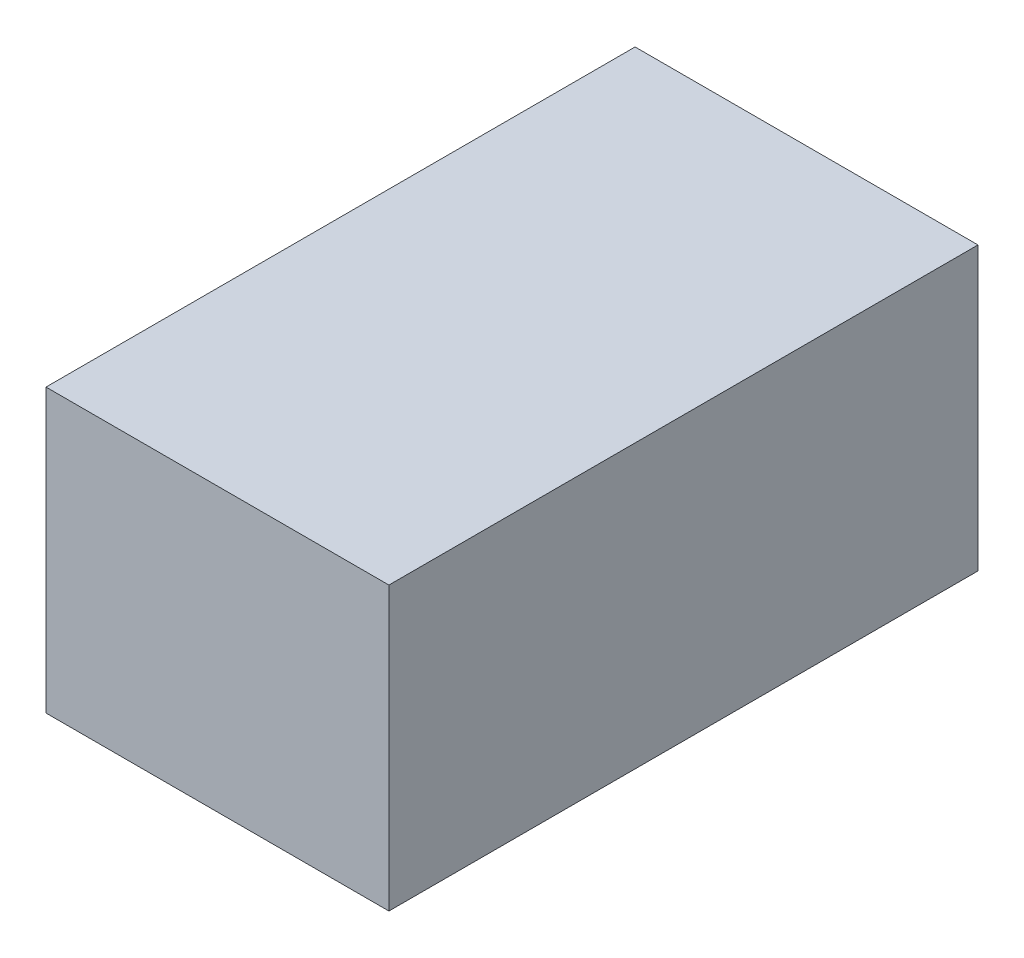
SolidWorks part; units mm, degrees
ref_plane "Front Plane" through (0, 0, 0) normal (0, 0, 1) x (1, 0, 0)
ref_plane "Top Plane" through (0, 0, 0) normal (0, 1, 0) x (1, 0, 0)
ref_plane "Right Plane" through (0, 0, 0) normal (1, 0, 0) x (0, 0, -1)
sketch "Sketch1" plane through (0, 0, 0) normal (0, 1, 0) x (1, 0, 0)
  line L1 (0, 0) -> (140.462, 0)
  line L2 (0, 0) -> (0, -241.3)
  line L3 (0, -241.3) -> (140.462, -241.3)
  line L4 (140.462, 0) -> (140.462, -241.3)
  dimension "D1" = 140.462
  dimension "D2" = 241.3
extrude "Boss-Extrude1" add sketch "Sketch1" along normal blind 115.65
sketch "Sketch2" plane through (0, 0, 0) normal (0, -1, 0) x (1, 0, 0)
  line L0 (0, 120.65) -> (140.462, 120.65) construction
  line L4 (140.462, 241.3) -> (140.462, 0) construction
  line L5 (0, 0) -> (0, 241.3) construction
  line L6 (70.231, 241.3) -> (70.231, 0) construction
  line L8 (140.462, 0) -> (0, 0) construction
  line L9 (0, 241.3) -> (140.462, 241.3) construction
  point P0 (70.231, 120.65)
  point P4 (0, 241.3)
  point P5 (70.231, 120.65)
  point P14 (70.231, 120.65)
  point P19 (-100.7207, 332.2945)
